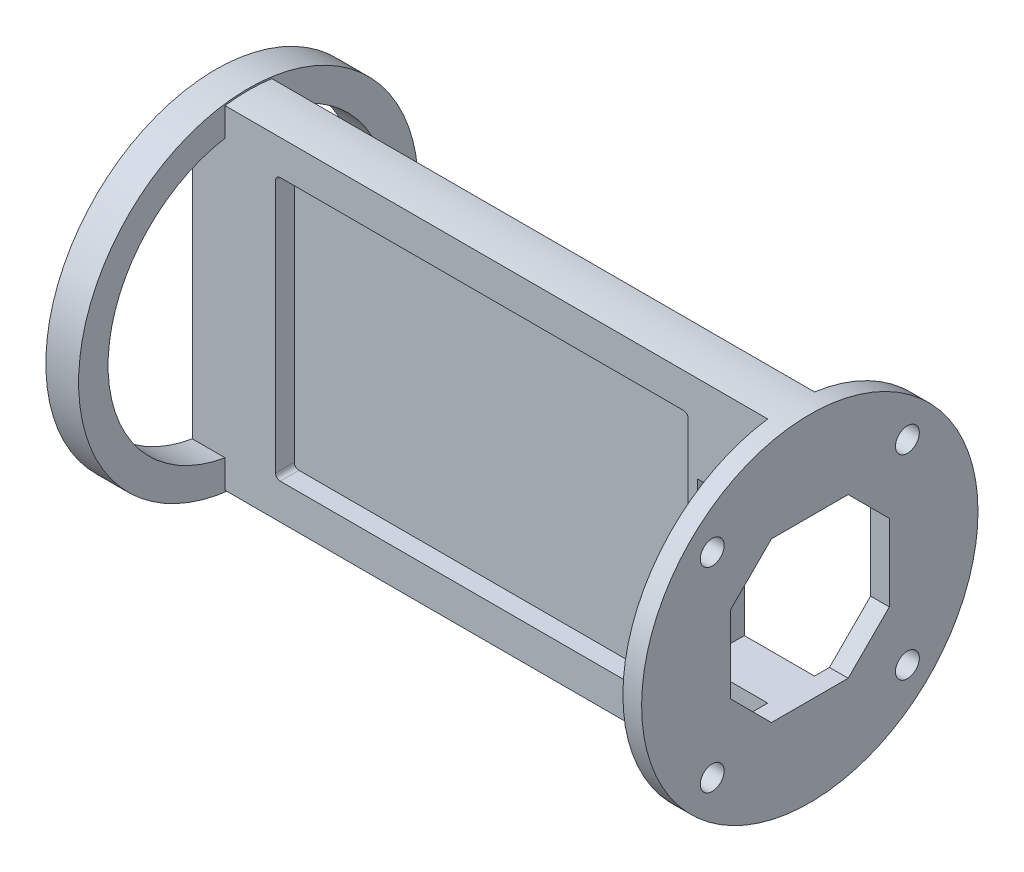
SolidWorks part; units mm, degrees
ref_plane "Front Plane" through (0, 0, 0) normal (0, 0, 1) x (1, 0, 0)
ref_plane "Top Plane" through (0, 0, 0) normal (0, 1, 0) x (1, 0, 0)
ref_plane "Right Plane" through (0, 0, 0) normal (1, 0, 0) x (0, 0, -1)
sketch "Sketch3" plane through (0, 0, 0) normal (0, 0, 1) x (1, 0, 0)
  line L0 (285.7488, 39.71) -> (285.7488, 3.758)
  line L1 (285.7488, 3.758) -> (80.7488, 3.758)
  line L2 (80.7488, 3.758) -> (80.7488, 19.6343)
  spline S0 degree 4 poles (-27.7192, -7.8553) (-27.5014, -7.7876) (-27.0667, -7.6528) (-26.2045, -7.3856) (-24.4548, -6.8463) (-22.0886, -6.1211) (-19.0086, -5.1883) (-15.5879, -4.1634) (-12.0469, -3.1177) (-8.7154, -2.1438) (-5.4871, -1.2149) (-3.2266, -0.5688) (-0.5536, 0.1859) (0.4881, 0.4785) (2.6576, 1.0849) (4.0523, 1.4709) (5.8579, 1.9693) (7.4437, 2.403) (9.5599, 2.9792) (12.0305, 3.6454) (14.9574, 4.4267) (18.2801, 5.3017) (21.6183, 6.1694) (25.7869, 7.2382) (30.7991, 8.5003) (35.8155, 9.7344) (40.8401, 10.9416) (45.8691, 12.1268) (50.9036, 13.2902) (56.7842, 14.6155) (65.1975, 16.4541) (73.6264, 18.2195) (82.0703, 19.9115) (92.2203, 21.8537) (109.1645, 24.9437) (127.868, 27.9778) (146.6331, 30.6047) (163.7338, 32.6585) (174.0045, 33.8015) (184.2848, 34.8552) (194.5761, 35.7972) (204.8769, 36.6272) (213.4665, 37.2443) (220.3412, 37.6932) (227.2189, 38.0972) (233.2386, 38.4115) (238.4005, 38.6528) (242.7017, 38.8352) (246.1452, 38.9699) (249.585, 39.0934) (253.0324, 39.2057) (256.468, 39.3067) (259.9241, 39.3966) (263.347, 39.4752) (266.8257, 39.5425) (270.2119, 39.5987) (273.7565, 39.6436) (276.6051, 39.6731) (279.4395, 39.6913) (281.5976, 39.7039) (285.1517, 39.711) (286.4225, 39.7109) (289.9962, 39.7036) (293.1094, 39.6857) (296.9947, 39.6557) (300.782, 39.6062) (305.3918, 39.5309) (308.4492, 39.4673) (311.2049, 39.4051) (312.9634, 39.3595) (313.8789, 39.3357) (314.3251, 39.3236) knots 0 0 0 0 0 0.00262 0.00524 0.01048 0.02096 0.03144 0.041921 0.052275 0.06263 0.072985 0.078162 0.083339 0.088305 0.093271 0.098237 0.103203 0.108168 0.113134 0.123066 0.132998 0.142929 0.152861 0.162793 0.182656 0.20252 0.212451 0.222383 0.242246 0.26211 0.281973 0.3217 0.341563 0.361427 0.401154 0.520334 0.560061 0.579924 0.599788 0.639515 0.679241 0.699105 0.718968 0.738832 0.758695 0.778558 0.78849 0.798422 0.808354 0.818285 0.828217 0.838149 0.84808 0.858012 0.867944 0.877875 0.887807 0.897739 0.902705 0.907671 0.917602 0.927839 0.932958 0.938076 0.95855 0.968912 0.979275 0.989637 0.994819 1 1 1 1 1 construction
  spline S1 degree 4 poles (80.7488, 19.6343) (82.3471, 19.9504) (85.6364, 20.5939) (92.3118, 21.8704) (109.1645, 24.9437) (127.868, 27.9778) (146.6331, 30.6047) (163.7338, 32.6585) (174.0045, 33.8015) (184.2848, 34.8552) (194.5761, 35.7972) (204.8769, 36.6272) (213.4665, 37.2443) (220.3412, 37.6932) (227.2189, 38.0972) (233.2386, 38.4115) (238.4005, 38.6528) (242.7017, 38.8352) (246.1452, 38.9699) (249.585, 39.0934) (253.0324, 39.2057) (256.468, 39.3067) (259.9241, 39.3966) (263.347, 39.4752) (266.8257, 39.5425) (270.2119, 39.5987) (273.7565, 39.6436) (276.6051, 39.6731) (279.4395, 39.6913) (281.5976, 39.7039) (283.943, 39.7086) (285.0303, 39.71) (285.7488, 39.71) knots 0.322773 0.322773 0.322773 0.322773 0.322773 0.341563 0.361427 0.401154 0.520334 0.560061 0.579924 0.599788 0.639515 0.679241 0.699105 0.718968 0.738832 0.758695 0.778558 0.78849 0.798422 0.808354 0.818285 0.828217 0.838149 0.84808 0.858012 0.867944 0.877875 0.887807 0.897739 0.902705 0.907671 0.917602 0.917602 0.917602 0.917602 0.917602
  dimension "D1" = 35.952
  dimension "D2" = 205
revolve "Revolve1" add sketch "Sketch3" angle 360 about L1
sketch "Sketch6" plane through (285.7488, 0, 0) normal (1, 0, 0) x (0, 0, -1)
  line L5 (-5, 39.67) -> (5, 39.67)
  line L6 (-5, 39.67) -> (-5, -32.154)
  line L15 (-5, -32.154) -> (5, -32.154)
  line L16 (5, 39.67) -> (5, -32.154)
  line L17 (0, -32.154) -> (0, 39.67) construction
  line L18 (-5, 3.758) -> (5, 3.758) construction
  line L19 (5, -32.154) -> (36.0764, -32.154)
  line L20 (5, -32.154) -> (5, 39.67)
  line L21 (5, 39.67) -> (36.0764, 39.67)
  line L22 (36.0764, -32.154) -> (36.0764, 39.67)
  line L23 (-5, 39.67) -> (-36.0314, 39.67)
  line L24 (-5, 39.67) -> (-5, -32.154)
  line L25 (-5, -32.154) -> (-36.0314, -32.154)
  line L26 (-36.0314, 39.67) -> (-36.0314, -32.154)
  point P0 (0, 3.758)
  point P1 (0, 3.758)
  circle M5 centre (0, 3.758) radius 35.952
  dimension "D1" = 5
extrude "Cut-Extrude1" cut sketch "Sketch6" against normal through all contours L6 M5 | L16 M5
sketch "Sketch8" plane through (285.7488, 0, 0) normal (1, 0, 0) x (0, 0, -1)
  line L0 (5, 39.3606) -> (5, -31.8446)
  line L6 (-5, -31.8446) -> (-5, 39.3606)
  circle A2 centre (0, 3.758) radius 35.952
  arc M19 (5, 39.3606) -> (-5, 39.3606) centre (0, 3.758) ccw
  line M20 (-5, 39.3606) -> (-5, -31.8446)
  arc M21 (-5, -31.8446) -> (5, -31.8446) centre (0, 3.758) ccw
  line M22 (5, -31.8446) -> (5, 39.3606)
  dimension "D1" = 71.904
extrude "Boss-Extrude2" add sketch "Sketch8" along normal blind 139.7 contours M22 M19 M20 M21
sketch "Sketch9" plane through (425.4488, 0, 0) normal (1, 0, 0) x (0, 0, -1)
  circle A1 centre (0, 3.758) radius 35.952
  dimension "D1" = 71.904
extrude "Boss-Extrude3" add sketch "Sketch9" along normal blind 4
sketch "Sketch10" plane through (429.4488, 0, 0) normal (1, 0, 0) x (0, 0, -1)
  line L4 (-17, -4.442) -> (-17, 11.958)
  line L5 (-8.2, 20.758) -> (8.2, 20.758)
  line L6 (17, 11.958) -> (17, -4.442)
  line L7 (8.2, -13.242) -> (-8.2, -13.242)
  line L8 (-17, 11.958) -> (-8.2, 20.758)
  line L9 (8.2, 20.758) -> (17, 11.958)
  line L10 (17, -4.442) -> (8.2, -13.242)
  line L11 (-8.2, -13.242) -> (-17, -4.442)
  dimension "D5" = 16.4
  dimension "D7" = 16.4
  dimension "D9" = 16.4
  dimension "D11" = 16.4
extrude "Cut-Extrude2" cut sketch "Sketch10" against normal blind 4
sketch "Sketch11" plane through (425.4488, 0, 0) normal (1, 0, 0) x (0, 0, -1)
  line L1 (-5, 20.758) -> (5, 20.758)
  line L2 (-5, 20.758) -> (-5, -13.242)
  line L3 (-5, -13.242) -> (5, -13.242)
  line L4 (5, 20.758) -> (5, -13.242)
  line L5 (0, -13.242) -> (0, 20.758) construction
  line L6 (-5, 3.758) -> (5, 3.758) construction
  point P0 (0, 3.758)
extrude "Cut-Extrude3" cut sketch "Sketch11" against normal blind 15
sketch "Sketch12" plane through (0, 0, 5) normal (0, 0, 1) x (1, 0, 0)
  line L0 (410.4488, 20.758) -> (410.4488, -13.242) construction
  line L1 (407.4488, -24.2556) -> (321.2488, -24.2556)
  line L2 (408.4488, -23.2556) -> (408.4488, 30.9444)
  line L3 (407.4488, 31.9444) -> (321.2488, 31.9444)
  line L4 (320.2488, -23.2556) -> (320.2488, 30.9444)
  arc A0 (320.2488, -23.2556) -> (321.2488, -24.2556) centre (321.2488, -23.2556) ccw
  arc A1 (407.4488, -24.2556) -> (408.4488, -23.2556) centre (407.4488, -23.2556) ccw
  arc A2 (408.4488, 30.9444) -> (407.4488, 31.9444) centre (407.4488, 30.9444) ccw
  arc A3 (321.2488, 31.9444) -> (320.2488, 30.9444) centre (321.2488, 30.9444) ccw
  point P10 (320.2488, -24.2556)
  point P13 (408.4488, -24.2556)
  point P16 (408.4488, 31.9444)
  dimension "D5" = 1
  dimension "D1" = 2
  dimension "D3" = 88.2
  dimension "D4" = 56.2
extrude "Raspberry Pi 5" cut sketch "Sketch12" against normal blind 4 contours A3 L3 A2 L2 A1 L1 A0 L4
sketch "Sketch13" plane through (0, 0, 5) normal (0, 0, 1) x (1, 0, 0)
  line L1 (294.9857, 8.9908) -> (262.3357, 8.9908)
  line L2 (295.9857, 9.9908) -> (295.9857, 33.5908)
  line L3 (294.9857, 34.5908) -> (262.3357, 34.5908)
  line L4 (261.3357, 9.9908) -> (261.3357, 33.5908)
  arc A0 (294.9857, 34.5908) -> (295.9857, 33.5908) centre (294.9857, 33.5908) cw
  arc A1 (295.9857, 9.9908) -> (294.9857, 8.9908) centre (294.9857, 9.9908) cw
  arc A2 (261.3357, 9.9908) -> (262.3357, 8.9908) centre (262.3357, 9.9908) ccw
  arc A3 (262.3357, 34.5908) -> (261.3357, 33.5908) centre (262.3357, 33.5908) ccw
  point P12 (295.9857, 8.9908)
  point P15 (261.3357, 8.9908)
  point P18 (261.3357, 34.5908)
  dimension "D5" = 1
  dimension "D1" = 34.65
  dimension "D2" = 25.6
extrude "GPS Slot" cut sketch "Sketch13" against normal blind 5.1
sketch "Sketch14" plane through (0, 0, 5) normal (0, 0, 1) x (1, 0, 0)
  line L1 (272.8797, -12.1069) -> (282.8797, -12.1069)
  line L2 (272.8797, -12.1069) -> (272.8797, -28.1069)
  line L3 (272.8797, -28.1069) -> (282.8797, -28.1069)
  line L4 (282.8797, -12.1069) -> (282.8797, -28.1069)
  line L5 (277.8797, -28.1069) -> (277.8797, -12.1069) construction
  line L6 (272.8797, -20.1069) -> (282.8797, -20.1069) construction
  point P0 (277.8797, -20.1069)
  dimension "D1" = 10
  dimension "D2" = 16
extrude "MPU" cut sketch "Sketch14" against normal through all
sketch "Sketch15" plane through (0, 0, 5) normal (0, 0, 1) x (1, 0, 0)
  line L1 (275.7173, 5.8289) -> (295.7173, 5.8289)
  line L2 (275.7173, 5.8289) -> (275.7173, -9.5111)
  line L3 (275.7173, -9.5111) -> (295.7173, -9.5111)
  line L4 (295.7173, 5.8289) -> (295.7173, -9.5111)
  line L5 (285.7173, -9.5111) -> (285.7173, 5.8289) construction
  line L6 (275.7173, -1.8411) -> (295.7173, -1.8411) construction
  point P0 (285.7173, -1.8411)
  dimension "D1" = 20
  dimension "D2" = 15.34
extrude "Altimeter" cut sketch "Sketch15" against normal blind 3.54 and the other way through all
sketch "Sketch16" plane through (0, 0, 5) normal (0, 0, 1) x (1, 0, 0)
  line L1 (101.7082, 16.3404) -> (163.9082, 16.3404)
  line L2 (101.7082, 16.3404) -> (101.7082, -9.1596)
  line L3 (101.7082, -9.1596) -> (163.9082, -9.1596)
  line L4 (163.9082, 16.3404) -> (163.9082, -9.1596)
  line L5 (132.8082, -9.1596) -> (132.8082, 16.3404) construction
  line L6 (101.7082, 3.5904) -> (163.9082, 3.5904) construction
  point P0 (132.8082, 3.5904)
  dimension "D1" = 62.2
  dimension "D2" = 25.5
extrude "PCA9685" cut sketch "Sketch16" against normal blind 2
sketch "Sketch17" plane through (0, 0, 5) normal (0, 0, 1) x (1, 0, 0)
  line L1 (208.4026, 2.9867) -> (258.4026, 2.9867)
  line L2 (208.4026, 2.9867) -> (208.4026, -24.0133)
  line L3 (208.4026, -24.0133) -> (258.4026, -24.0133)
  line L4 (258.4026, 2.9867) -> (258.4026, -24.0133)
  line L5 (233.4026, -24.0133) -> (233.4026, 2.9867) construction
  line L6 (208.4026, -10.5133) -> (258.4026, -10.5133) construction
  point P0 (233.4026, -10.5133)
  dimension "D1" = 50
  dimension "D2" = 27
extrude "ESP-32 (1)" cut sketch "Sketch17" against normal blind 5
sketch "Sketch18" plane through (0, 0, -5) normal (0, 0, -1) x (-1, 0, 0)
  line L1 (-350.4488, 35.0173) -> (-405.4488, 35.0173)
  line L2 (-350.4488, 35.0173) -> (-350.4488, 4.9173)
  line L3 (-350.4488, 4.9173) -> (-405.4488, 4.9173)
  line L4 (-405.4488, 35.0173) -> (-405.4488, 4.9173)
  line L5 (-377.9488, 4.9173) -> (-377.9488, 35.0173) construction
  line L6 (-350.4488, 19.9673) -> (-405.4488, 19.9673) construction
  point P0 (-377.9488, 19.9673)
  dimension "D1" = 55
  dimension "D2" = 30.1
sketch "Sketch21" plane through (0, 0, -5) normal (0, 0, -1) x (-1, 0, 0)
  line L1 (-350.4488, 2.5987) -> (-405.4488, 2.5987)
  line L2 (-350.4488, 2.5987) -> (-350.4488, -27.5013)
  line L3 (-350.4488, -27.5013) -> (-405.4488, -27.5013)
  line L4 (-405.4488, 2.5987) -> (-405.4488, -27.5013)
  line L5 (-377.9488, -27.5013) -> (-377.9488, 2.5987) construction
  line L6 (-350.4488, -12.4513) -> (-405.4488, -12.4513) construction
  point P0 (-377.9488, -12.4513)
  dimension "D1" = 55
  dimension "D2" = 30.1
extrude "Battery 1" cut sketch "Sketch18" against normal blind 3.5
extrude "Battery 2" cut sketch "Sketch21" against normal blind 3.5
sketch "Sketch24" plane through (0, 0, -5) normal (0, 0, -1) x (-1, 0, 0)
  line L1 (-258.8418, 32.0557) -> (-208.8418, 32.0557)
  line L2 (-258.8418, 32.0557) -> (-258.8418, 5.0557)
  line L3 (-258.8418, 5.0557) -> (-208.8418, 5.0557)
  line L4 (-208.8418, 32.0557) -> (-208.8418, 5.0557)
  line L5 (-233.8418, 5.0557) -> (-233.8418, 32.0557) construction
  line L6 (-258.8418, 18.5557) -> (-208.8418, 18.5557) construction
  point P0 (-233.8418, 18.5557)
  dimension "D1" = 50
  dimension "D2" = 27
extrude "ESP-32 (Meshtastic)" cut sketch "Sketch24" against normal blind 5
sketch "Sketch25" plane through (0, 0, -5) normal (0, 0, -1) x (-1, 0, 0)
  line L1 (-334.5276, 27.4269) -> (-313.4276, 27.4269)
  line L2 (-334.5276, 27.4269) -> (-334.5276, -15.6731)
  line L3 (-334.5276, -15.6731) -> (-313.4276, -15.6731)
  line L4 (-313.4276, 27.4269) -> (-313.4276, -15.6731)
  line L5 (-323.9776, -15.6731) -> (-323.9776, 27.4269) construction
  line L6 (-334.5276, 5.8769) -> (-313.4276, 5.8769) construction
  point P0 (-323.9776, 5.8769)
  dimension "D1" = 43.1
  dimension "D2" = 21.1
extrude "Step Down" cut sketch "Sketch25" against normal blind 1
sketch "Sketch26" plane through (0, 0, -5) normal (0, 0, -1) x (-1, 0, 0)
  line L1 (-190.4787, 16.6983) -> (-140.4787, 16.6983)
  line L2 (-190.4787, 16.6983) -> (-190.4787, -10.3017)
  line L3 (-190.4787, -10.3017) -> (-140.4787, -10.3017)
  line L4 (-140.4787, 16.6983) -> (-140.4787, -10.3017)
  line L5 (-165.4787, -10.3017) -> (-165.4787, 16.6983) construction
  line L6 (-190.4787, 3.1983) -> (-140.4787, 3.1983) construction
  point P0 (-165.4787, 3.1983)
  dimension "D1" = 50
  dimension "D2" = 27
extrude "ESP-32 (2)" cut sketch "Sketch26" against normal blind 5
sketch "Sketch27" plane through (429.4488, 0, 0) normal (1, 0, 0) x (0, 0, -1)
  circle A0 centre (0, 3.758) radius 36.3
  circle A1 centre (0, 3.758) radius 30
  dimension "D1" = 72.6
extrude "Boss-Extrude4" add sketch "Sketch27" against normal blind 7 from offset 120 offset against normal yes
sketch "Sketch29" plane through (429.4488, 0, 0) normal (1, 0, 0) x (0, 0, -1)
  circle A0 centre (0, 3.758) radius 36.3
extrude "Cut-Extrude4" cut sketch "Sketch29" against normal through all from offset 127 offset against normal yes
sketch "Sketch30" plane through (302.4488, 0, 0) normal (-1, 0, 0) x (0, 0, 1)
  line L1 (-2, 15.958) -> (2, 15.958)
  line L2 (-2, 15.958) -> (-2, -8.442)
  line L3 (-2, -8.442) -> (2, -8.442)
  line L4 (2, 15.958) -> (2, -8.442)
  line L5 (0, -8.442) -> (0, 15.958) construction
  line L6 (-2, 3.758) -> (2, 3.758) construction
  point P0 (0, 3.758)
  dimension "D1" = 2
  dimension "D2" = 12.2
extrude "Cut-Extrude5" cut sketch "Sketch30" against normal blind 5.1
sketch "Sketch31" plane through (429.4488, 0, 0) normal (1, 0, 0) x (0, 0, -1)
  circle A0 centre (20.8597, 24.6176) radius 2.55
  circle A1 centre (-20.8597, 24.6176) radius 2.55
  circle A2 centre (-20.8597, -17.1017) radius 2.55
  circle A3 centre (20.8597, -17.1017) radius 2.55
  point P11 (0, 3.758)
  dimension "D2" = 5.1
  dimension "D1" = 4
extrude "Cut-Extrude6" cut sketch "Sketch31" against normal up to next
